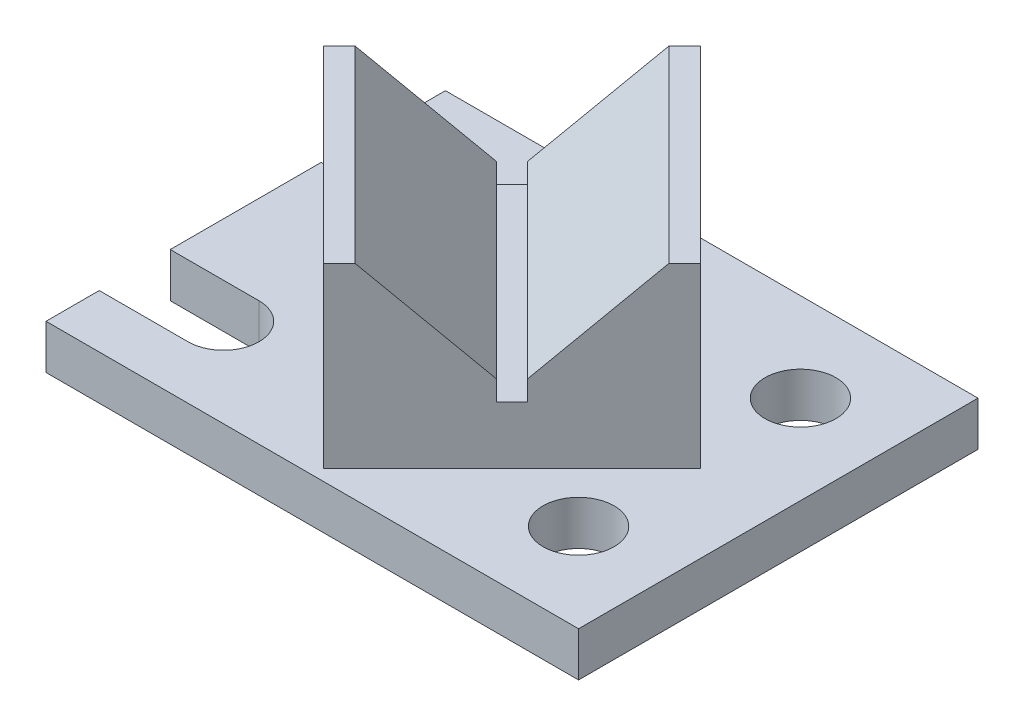
SolidWorks part; units mm, degrees
material "2014 Alloy"
ref_plane "Front Plane" through (0, 0, 0) normal (0, 0, 1) x (1, 0, 0)
ref_plane "Top Plane" through (0, 0, 0) normal (0, 1, 0) x (1, 0, 0)
ref_plane "Right Plane" through (0, 0, 0) normal (1, 0, 0) x (0, 0, -1)
sketch "Croquis1" plane through (0, 0, 0) normal (0, 1, 0) x (1, 0, 0)
  line L1 (-76.2, -57.15) -> (76.2, -57.15)
  line L2 (-76.2, -57.15) -> (-76.2, 57.15)
  line L3 (-76.2, 57.15) -> (76.2, 57.15)
  line L4 (76.2, -57.15) -> (76.2, 57.15)
  line L5 (-76.2, -57.15) -> (76.2, 57.15) construction
  line L6 (-76.2, 57.15) -> (76.2, -57.15) construction
  point P0 (0, 0)
  dimension "D1" = 114.3
  dimension "D2" = 152.4
extrude "Saliente-Extruir1" add sketch "Croquis1" along normal blind 12.7
sketch "Croquis3" plane through (0, 12.7, 0) normal (0, 1, 0) x (1, 0, 0)
  line L0 (76.2, -57.15) -> (76.2, 57.15) construction
  line L1 (-76.2, -57.15) -> (76.2, -57.15) construction
  line L2 (-76.2, 57.15) -> (-76.2, -57.15) construction
  line L3 (-76.2, -21.59) -> (-50.8, -21.59)
  line L4 (-76.2, -21.59) -> (-76.2, -41.91)
  line L5 (-76.2, -41.91) -> (-50.8, -41.91)
  line L6 (-50.8, -21.59) -> (-50.8, -41.91) construction
  line L7 (-76.2, -31.75) -> (-50.8, -31.75) construction
  circle A0 centre (50.8, -31.75) radius 10.16
  arc A1 (-50.8, -21.59) -> (-50.8, -41.91) centre (-50.8, -31.75) cw
  dimension "D3" = 20.32
  dimension "D1" = 25.4
  dimension "D2" = 25.4
  dimension "D4" = 25.4
  dimension "D5" = 20.32
  dimension "D6" = 25.4
extrude "Cortar-Extruir1" cut sketch "Croquis3" against normal through all
mirror "Simetría1" about plane through (0, 0, 0) normal (0, 0, 1) of "Cortar-Extruir1"
sketch "Croquis4" plane through (0, 12.7, 0) normal (0, 1, 0) x (1, 0, 0)
  line L1 (53.8815, 0) -> (0, -53.8815)
  line L2 (53.8815, 0) -> (0, 53.8815)
  line L3 (0, 53.8815) -> (-53.8815, 0)
  line L4 (0, -53.8815) -> (-53.8815, 0)
  line L5 (53.8815, 0) -> (-53.8815, 0) construction
  line L6 (0, 53.8815) -> (0, -53.8815) construction
  point P0 (0, 0)
  dimension "D1" = 76.2
extrude "Saliente-Extruir2" add sketch "Croquis4" along normal blind 50.8
sketch "Croquis5" plane through (26.9408, 0, 26.9408) normal (0.7071, 0, 0.7071) x (0.7071, 0, -0.7071)
  line L0 (0, 63.5) -> (0, 12.7) construction
  line L1 (-38.1, 63.5) -> (38.1, 63.5) construction
  line L2 (-38.1, 12.7) -> (38.1, 12.7) construction
  line L3 (-31.75, 63.5) -> (31.75, 63.5)
  line L4 (31.75, 63.5) -> (3.175, 34.925)
  line L5 (3.175, 34.925) -> (3.175, 29.21)
  line L6 (3.175, 29.21) -> (-3.175, 29.21)
  line L7 (-3.175, 34.925) -> (-3.175, 29.21)
  line L8 (-31.75, 63.5) -> (-3.175, 34.925)
  line L9 (-94.2927, 12.7) -> (13.4704, 12.7) construction
  point P9 (0, 63.5)
  point P13 (0, 29.21)
  dimension "D1" = 6.35
  dimension "D2" = 90
  dimension "D3" = 16.51
  dimension "D4" = 6.35
extrude "Cortar-Extruir2" cut sketch "Croquis5" against normal through all
